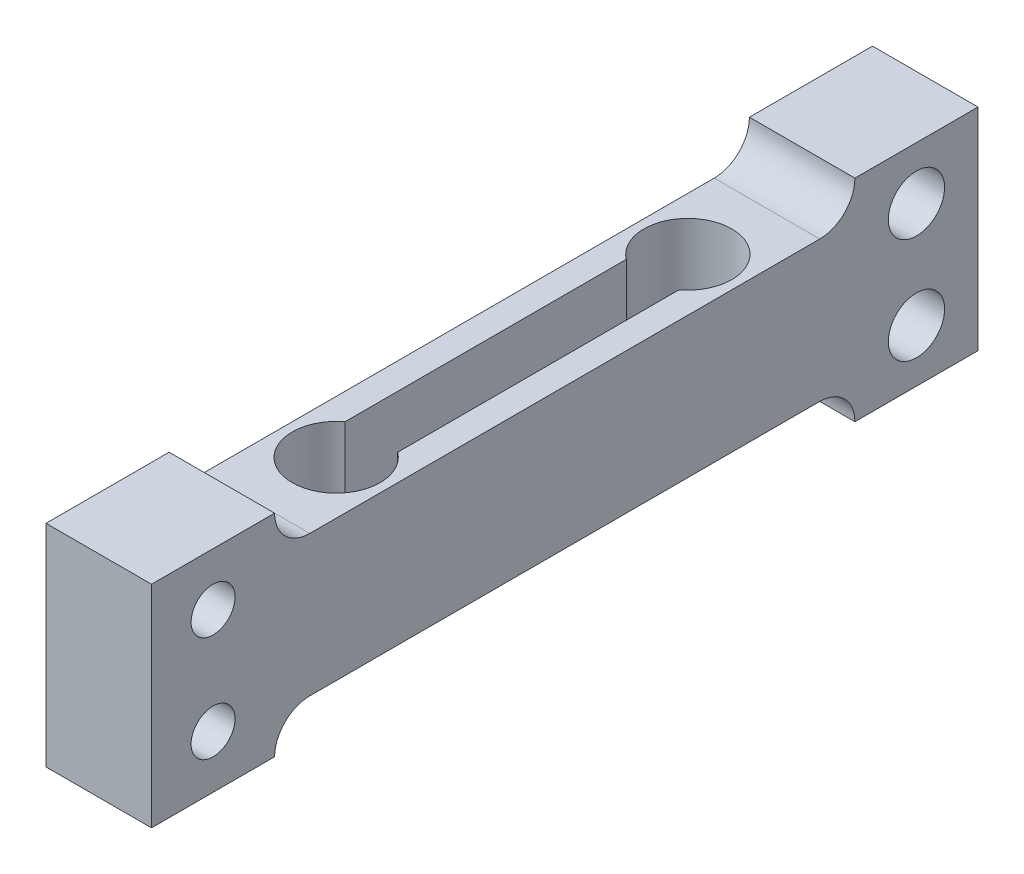
SolidWorks part; units mm, degrees
ref_plane "Front Plane" through (0, 0, 0) normal (0, 0, 1) x (1, 0, 0)
ref_plane "Top Plane" through (0, 0, 0) normal (0, 1, 0) x (1, 0, 0)
ref_plane "Right Plane" through (0, 0, 0) normal (1, 0, 0) x (0, 0, -1)
sketch "Sketch1" plane through (0, 0, 0) normal (1, 0, 0) x (0, 0, -1)
  line L1 (-23.5, -6) -> (23.5, -6)
  line L2 (-23.5, -6) -> (-23.5, 6)
  line L3 (-23.5, 6) -> (23.5, 6)
  line L4 (23.5, -6) -> (23.5, 6)
  line L5 (-23.5, -6) -> (23.5, 6) construction
  line L6 (-23.5, 6) -> (23.5, -6) construction
  point P0 (0, 0)
  dimension "D1" = 47
  dimension "D2" = 12
extrude "Boss-Extrude1" add sketch "Sketch1" along normal blind 6
sketch "Sketch3" plane through (6, 0, 0) normal (1, 0, 0) x (0, 0, -1)
  line L0 (0, 6) -> (0, -6) construction
  line L1 (23.5, 6) -> (-23.5, 6) construction
  line L2 (-23.5, -6) -> (23.5, -6) construction
  line L3 (-23.5, 0) -> (23.5, 0) construction
  line L4 (-23.5, 6) -> (-23.5, -6) construction
  line L5 (23.5, -6) -> (23.5, 6) construction
  line L6 (16.5, 6) -> (-16.5, 6)
  line L7 (-14.5, 4) -> (14.5, 4)
  line L9 (-14.5, -4) -> (14.5, -4)
  line L10 (16.5, -6) -> (-16.5, -6)
  arc A0 (-16.5, 6) -> (-14.5, 4) centre (-14.5, 6) ccw
  arc A1 (16.5, 6) -> (14.5, 4) centre (14.5, 6) cw
  arc A2 (16.5, -6) -> (14.5, -4) centre (14.5, -6) ccw
  arc A3 (-16.5, -6) -> (-14.5, -4) centre (-14.5, -6) cw
  point P20 (0, 4)
  point P26 (0, -4)
  dimension "D1" = 2
  dimension "D2" = 33
extrude "Cut-Extrude2" cut sketch "Sketch3" against normal through all
sketch "Sketch4" plane through (6, 0, 0) normal (1, 0, 0) x (0, 0, -1)
  line L0 (20, 3) -> (20, -3) construction
  line L1 (0, 0) -> (20, 0) construction
  circle A0 centre (20, 3) radius 1.6
  circle A1 centre (20, -3) radius 1.6
  dimension "D1" = 3.2
  dimension "D2" = 20
  dimension "D3" = 6
extrude "Cut-Extrude3" cut sketch "Sketch4" against normal through all
hole_wizard "M3x0.5 Tapped Hole1" positions "Sketch5" profile "Sketch6" tap size "M3x0.5" standard "ANSI Metric"
sketch "Sketch5" plane through (6, 0, 0) normal (1, 0, 0) x (0, 0, -1)
  line L0 (-20, -3) -> (-20, 3) construction
  line L1 (-20, 0) -> (0, 0) construction
  point P0 (-20, 3)
  point P2 (-20, -3)
  dimension "D1" = 20
  dimension "D2" = 6
sketch "Sketch6" plane through (6, 3, 20) normal (0, 1, 0) x (0, 0, -1)
  line L0 (0, 0) -> (0, 8.2511)
  line L1 (0, 8.2511) -> (1.25, 7.5)
  line L2 (1.25, 7.5) -> (1.25, 0)
  line L5 (1.25, 0) -> (0, 0)
  line L10 (0, 8.2511) -> (-1.25, 7.5) construction
  line L11 (0, -6.35) -> (0, 107.95) construction
  dimension "Tap Drill Dia." = 2.5
  dimension "Tap Drill Depth" = 7.5
  dimension "Drill Angle" = 118
cosmetic thread "Hole Thread1" parameters "D1"=6, "D2"=3
cosmetic thread "Hole Thread2" parameters "D1"=6, "D2"=3
sketch "Sketch8" plane through (0, -4, 0) normal (0, -1, 0) x (1, 0, 0)
  line L0 (0, 0) -> (6, 0) construction
  line L1 (0, -14.5) -> (0, 14.5) construction
  line L2 (6, -14.5) -> (6, 14.5) construction
  line L3 (3, 10) -> (3, -10) construction
  line L6 (4.5, 8) -> (4.5, -8)
  line L8 (1.5, -8) -> (1.5, 8)
  arc A0 (4.5, 8) -> (1.5, 8) centre (3, 10) ccw
  arc A1 (1.5, -8) -> (4.5, -8) centre (3, -10) ccw
  point P7 (3, 0)
  point P8 (3, 0)
  dimension "D2" = 5
  dimension "D1" = 20
  dimension "D3" = 1.5
  dimension "D4" = 1.5
extrude "Cut-Extrude4" cut sketch "Sketch8" against normal through all
equation "\"D4@Sketch8\"=\"D3@Sketch8\""
